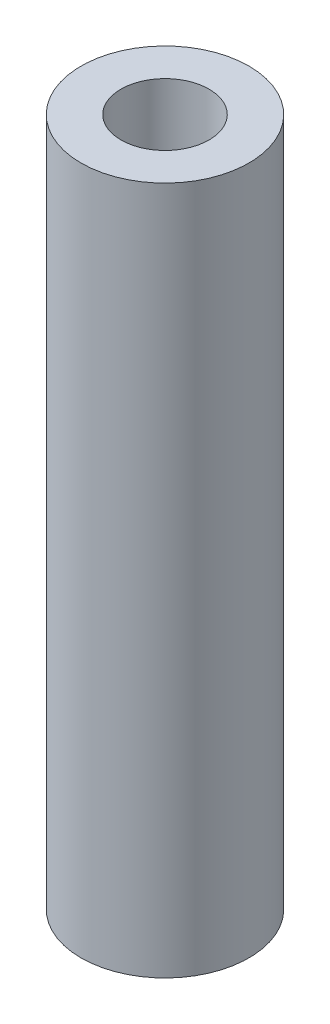
SolidWorks part; units mm, degrees
ref_plane "正面" through (0, 0, 0) normal (0, 0, 1) x (1, 0, 0)
ref_plane "平面" through (0, 0, 0) normal (0, 1, 0) x (1, 0, 0)
ref_plane "右側面" through (0, 0, 0) normal (1, 0, 0) x (0, 0, -1)
sketch "ｽｹｯﾁ1" plane through (0, 0, 0) normal (0, 1, 0) x (1, 0, 0)
  circle A0 centre (0, 0) radius 3.05
  circle A1 centre (0, 0) radius 1.6
  dimension "D1" = 3.2
  dimension "D2" = 6.1
extrude "ﾎﾞｽ - 押し出し1" add sketch "ｽｹｯﾁ1" along normal blind 25
